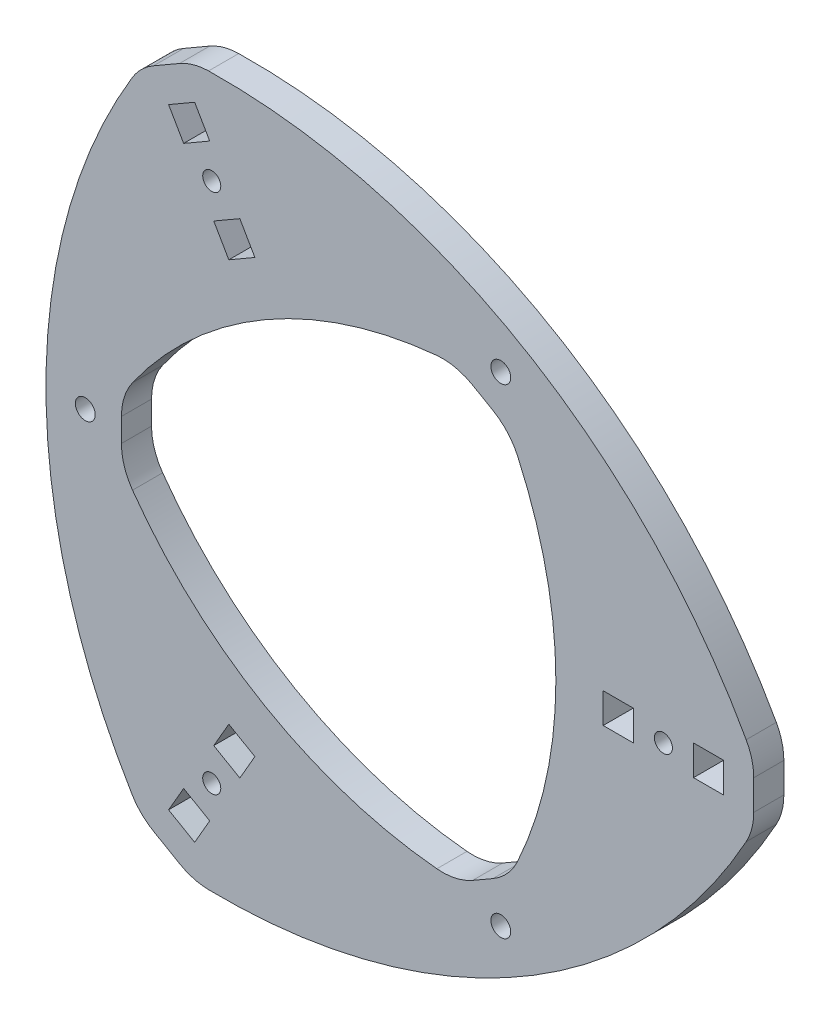
SolidWorks part; units mm, degrees
ref_plane "Plan de face" through (0, 0, 0) normal (0, 0, 1) x (1, 0, 0)
ref_plane "Plan de dessus" through (0, 0, 0) normal (0, 1, 0) x (1, 0, 0)
ref_plane "Plan de droite" through (0, 0, 0) normal (1, 0, 0) x (0, 0, -1)
sketch "Esquisse1" plane through (0, 0, 0) normal (0, 0, 1) x (1, 0, 0)
  line L0 (0, 0) -> (50, 0) construction
  line L1 (0, 0) -> (-25, -43.3013) construction
  line L2 (0, 0) -> (-25, 43.3013) construction
  line L3 (-36.8301, 53.7917) -> (-28.1699, 58.7917)
  line L4 (65, 5) -> (65, -5)
  line L5 (-28.1699, -58.7917) -> (-36.8301, -53.7917)
  line L6 (15.6699, 37.141) -> (24.3301, 32.141)
  line L7 (24.3301, -32.141) -> (15.6699, -37.141)
  line L8 (-40, -5) -> (-40, 5)
  circle A1 centre (23, 39.8372) radius 1.65
  circle A2 centre (23, -39.8372) radius 1.65
  circle A3 centre (-46, 0) radius 1.65
  arc A4 (-28.1699, 58.7917) -> (65, 5) centre (-23.7348, -41.11) cw
  arc A5 (65, -5) -> (-28.1699, -58.7917) centre (-23.7348, 41.11) cw
  arc A6 (-36.8301, -53.7917) -> (-36.8301, 53.7917) centre (47.4697, 0) cw
  circle A7 centre (0, 0) radius 41 construction
  arc A8 (15.6699, 37.141) -> (-40, 5) centre (18.9274, -32.7831) ccw
  arc A9 (24.3301, -32.141) -> (24.3301, 32.141) centre (-37.8547, 0) ccw
  arc A10 (-40, -5) -> (15.6699, -37.141) centre (18.9274, 32.7831) ccw
  point P7 (0, 0)
  point P14 (0, 0)
  point P21 (0, 0)
  point P29 (0, 0)
  point P33 (0, 0)
  point P41 (0, 0)
  line B0 (45, 2.5) -> (40, 2.5)
  line B1 (45, 2.5) -> (45, -2.5)
  line B2 (45, -2.5) -> (40, -2.5)
  line B3 (40, 2.5) -> (40, -2.5)
  line B4 (55, 2.5) -> (60, 2.5)
  line B5 (55, 2.5) -> (55, -2.5)
  line B6 (55, -2.5) -> (60, -2.5)
  line B7 (60, 2.5) -> (60, -2.5)
  circle B8 centre (50, 0) radius 1.5
  line B9 (-25.3349, 48.8814) -> (-27.8349, 53.2115)
  line B10 (-25.3349, 48.8814) -> (-29.6651, 46.3814)
  line B11 (-29.6651, 46.3814) -> (-32.1651, 50.7115)
  line B12 (-27.8349, 53.2115) -> (-32.1651, 50.7115)
  line B13 (-20.3349, 40.2211) -> (-17.8349, 35.891)
  line B14 (-20.3349, 40.2211) -> (-24.6651, 37.7211)
  line B15 (-24.6651, 37.7211) -> (-22.1651, 33.391)
  line B16 (-17.8349, 35.891) -> (-22.1651, 33.391)
  circle B17 centre (-25, 43.3013) radius 1.5
  line B18 (-29.6651, -46.3814) -> (-32.1651, -50.7115)
  line B19 (-29.6651, -46.3814) -> (-25.3349, -48.8814)
  line B20 (-25.3349, -48.8814) -> (-27.8349, -53.2115)
  line B21 (-32.1651, -50.7115) -> (-27.8349, -53.2115)
  line B22 (-24.6651, -37.7211) -> (-22.1651, -33.391)
  line B23 (-24.6651, -37.7211) -> (-20.3349, -40.2211)
  line B24 (-20.3349, -40.2211) -> (-17.8349, -35.891)
  line B25 (-22.1651, -33.391) -> (-17.8349, -35.891)
  circle B26 centre (-25, -43.3013) radius 1.5
  dimension "D1" = 50
  dimension "D3" = 3.3
  dimension "D9" = 100
  dimension "D11" = 82
  dimension "D16" = 70
  dimension "D2" = 3
  dimension "D4" = 46
  dimension "D6" = 5
  dimension "D8" = 10
  dimension "D12" = 10
  dimension "D13" = 6
  dimension "D5" = 3
  dimension "D7" = 3
  dimension "D10" = 3
  dimension "D14" = 3
  dimension "D15" = 3
sketch_block_instance "Trou M3 plots 5mm-1"
sketch_block "Trou M3 plots 5mm" parameters "D2"=3, "D1"=5, "D3"=5, "D4"=10
sketch_block_instance "Trou M3 plots 5mm-3"
sketch_block_instance "Trou M3 plots 5mm-4"
extrude "Boss.-Extru.1" add sketch "Esquisse1" along normal blind 5
fillet "Fillet1" radius 10 12 edges at (24.3301, -32.141, 2.5) (15.6699, -37.141, 2.5) (-40, -5, 2.5) (-40, 5, 2.5) (65, 5, 2.5) (-28.1699, -58.7917, 2.5) (-36.8301, -53.7917, 2.5) (-36.8301, 53.7917, 2.5) (-28.1699, 58.7917, 2.5) (15.6699, 37.141, 2.5) (24.3301, 32.141, 2.5) (65, -5, 2.5)
